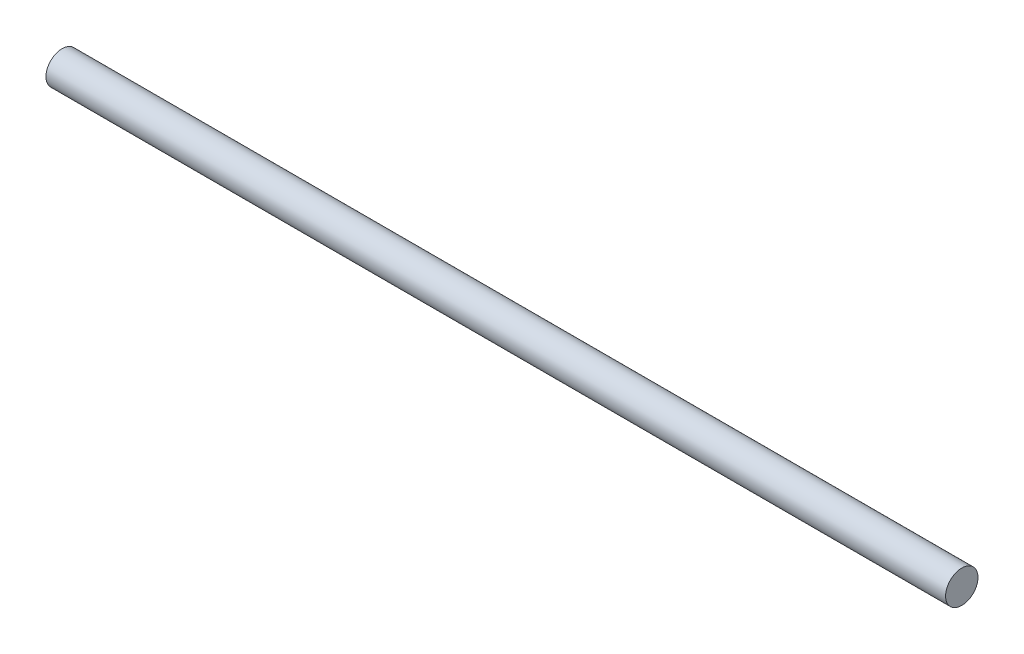
SolidWorks part; units mm, degrees
ref_plane "Front Plane" through (0, 0, 0) normal (1, 0, 0) x (0, 1, 0)
ref_plane "Top Plane" through (0, 0, 0) normal (0, 0, 1) x (0, 1, 0)
ref_plane "Right Plane" through (0, 0, 0) normal (0, 1, 0) x (-1, 0, 0)
sketch "Sketch1" plane through (0, 0, 0) normal (0, 1, 0) x (-1, 0, 0)
  line L1 (-222, 0) -> (222, 0)
  line L2 (-222, 0) -> (-222, 8)
  line L3 (-222, 8) -> (222, 8)
  line L4 (222, 0) -> (222, 8)
  point P4 (0, 0)
  dimension "D1" = 8
  dimension "D2" = 444
revolve "Revolve1" add sketch "Sketch1" angle 360 about L1
